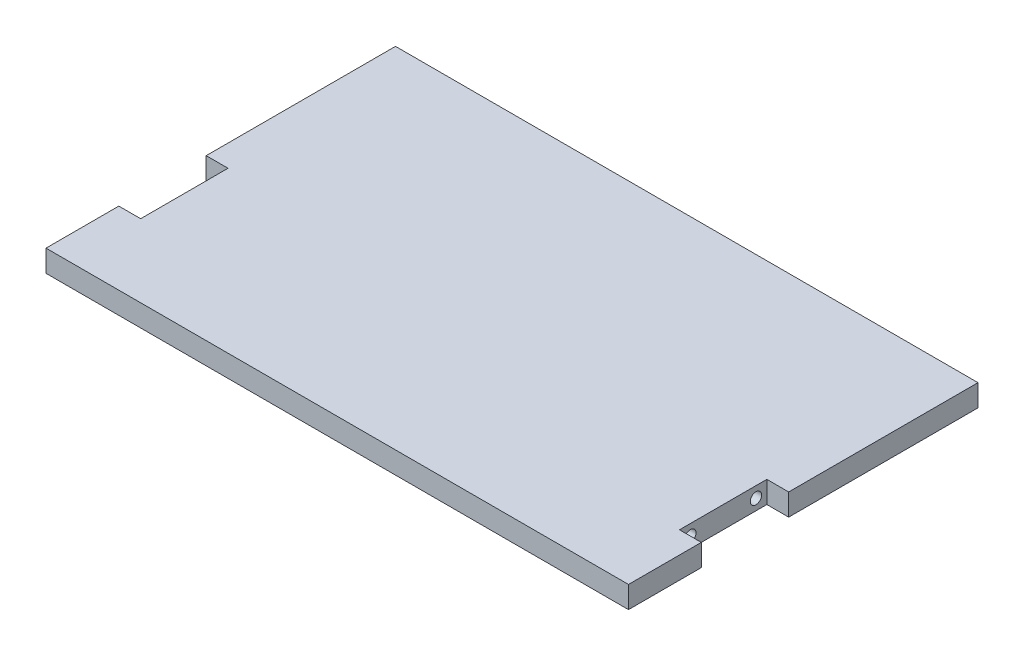
SolidWorks part; units mm, degrees
material "PE High Density"
ref_plane "Front Plane" through (0, 0, 0) normal (0, 0, 1) x (1, 0, 0)
ref_plane "Top Plane" through (0, 0, 0) normal (0, 1, 0) x (1, 0, 0)
ref_plane "Right Plane" through (0, 0, 0) normal (1, 0, 0) x (0, 0, -1)
sketch "Sketch1" plane through (0, 0, 0) normal (0, 1, 0) x (1, 0, 0)
  line L1 (-127, 127) -> (127, 127)
  line L2 (-127, 127) -> (-127, -127)
  line L3 (-127, -127) -> (127, -127)
  line L4 (127, 127) -> (127, -127)
  line L5 (-127, 127) -> (127, -127) construction
  line L6 (-127, -127) -> (127, 127) construction
  point P0 (0, 0)
  dimension "D1" = 254
  dimension "D2" = 254
extrude "Boss-Extrude1" add sketch "Sketch1" along normal blind 9.525
sketch "Sketch7" plane through (0, 9.525, 0) normal (0, 1, 0) x (1, 0, 0)
  line L0 (127, 127) -> (-127, 127) construction
  line L1 (-127, 25.4) -> (-41.0029, 25.4) construction
  line L2 (0, 0) -> (0, -32.6591) construction
  line L3 (-127, 44.45) -> (-117.475, 44.45)
  line L4 (-127, 44.45) -> (-127, 6.35)
  line L5 (-127, 6.35) -> (-117.475, 6.35)
  line L6 (-117.475, 44.45) -> (-117.475, 6.35)
  line L7 (117.475, 44.45) -> (117.475, 6.35)
  line L8 (127, 6.35) -> (117.475, 6.35)
  line L9 (127, 44.45) -> (127, 6.35)
  line L10 (127, 44.45) -> (117.475, 44.45)
  point P10 (-117.475, 25.4)
  dimension "D1" = 38.1
  dimension "D2" = 9.525
  dimension "D5" = 82.55
extrude "Cut-Extrude4" cut sketch "Sketch7" against normal through all
hole_wizard "#10 (0.1935) Diameter Hole1" positions "Sketch11" profile "Sketch10" hole size "#10" standard "ANSI Inch"
sketch "Sketch11" plane through (117.475, 0, 0) normal (1, 0, 0) x (0, 0, -1)
  line L0 (44.45, 0) -> (44.45, 9.525) construction
  point P0 (11.1125, 4.7625)
  point P3 (39.6875, 4.7625)
  point P8 (44.45, 4.7625)
  dimension "D1" = 28.575
  dimension "D2" = 4.7625
sketch "Sketch10" plane through (117.475, 4.7625, -11.1125) normal (0, 1, 0) x (0, 0, -1)
  line L0 (0, 0) -> (0, 14.1766)
  line L1 (0, 14.1766) -> (2.4574, 12.7)
  line L2 (2.4574, 12.7) -> (2.4574, 0)
  line L5 (2.4574, 0) -> (0, 0)
  line L10 (0, 14.1766) -> (-2.4575, 12.7) construction
  line L11 (0, -6.35) -> (0, 107.95) construction
  dimension "Hole Dia." = 4.9149
  dimension "Hole Depth" = 12.7
  dimension "Drill Angle" = 118
hole_wizard "#10 (0.1935) Diameter Hole3" positions "Sketch15" profile "Sketch14" hole size "#10" standard "ANSI Inch"
sketch "Sketch15" plane through (-117.475, 0, 0) normal (-1, 0, 0) x (0, 0, 1)
  line L0 (-44.45, 0) -> (-44.45, 9.525) construction
  point P0 (-39.6875, 4.7625)
  point P3 (-11.1125, 4.7625)
  point P8 (-44.45, 4.7625)
  dimension "D1" = 4.7625
  dimension "D2" = 28.575
sketch "Sketch14" plane through (-117.475, 4.7625, -39.6875) normal (0, 1, 0) x (0, 0, 1)
  line L0 (0, 0) -> (0, 14.1766)
  line L1 (0, 14.1766) -> (2.4574, 12.7)
  line L2 (2.4574, 12.7) -> (2.4574, 0)
  line L5 (2.4574, 0) -> (0, 0)
  line L10 (0, 14.1766) -> (-2.4574, 12.7) construction
  line L11 (0, -6.35) -> (0, 107.95) construction
  dimension "Hole Dia." = 4.9149
  dimension "Hole Depth" = 12.7
  dimension "Drill Angle" = 118
sketch "Sketch16" plane through (0, 9.525, 0) normal (0, 1, 0) x (1, 0, 0)
  line L1 (-127, -127) -> (127, -127)
  line L2 (-127, -127) -> (-127, -25.4)
  line L3 (-127, -25.4) -> (127, -25.4)
  line L4 (127, -127) -> (127, -25.4)
  dimension "D1" = 101.6
extrude "Cut-Extrude5" cut sketch "Sketch16" against normal through all
